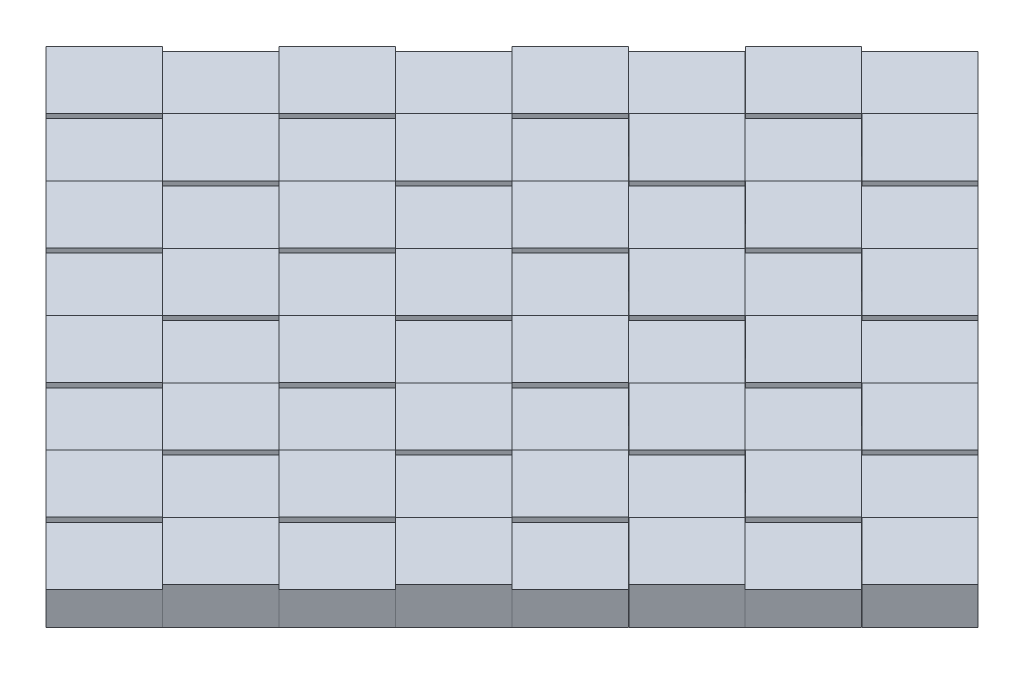
SolidWorks part; units mm, degrees
ref_plane "Front Plane" through (0, 0, 0) normal (0, 0, 1) x (1, 0, 0)
ref_plane "Top Plane" through (0, 0, 0) normal (0, 1, 0) x (1, 0, 0)
ref_plane "Right Plane" through (0, 0, 0) normal (1, 0, 0) x (0, 0, -1)
sketch "Sketch1" plane through (0, 0, 0) normal (0, 1, 0) x (1, 0, 0)
  line L0 (0, 0) -> (21.4596, 0) construction
  line L1 (150, 150) -> (-150, 150)
  line L2 (150, 150) -> (150, -150)
  line L3 (150, -150) -> (-150, -150)
  line L4 (-150, 150) -> (-150, -150)
  line L5 (0, 0) -> (0, 15.0297) construction
  dimension "D1" = 300
extrude "Boss-Extrude1" add sketch "Sketch1" along normal blind 15
sketch "Sketch6" plane through (0, 15, 0) normal (0, 1, 0) x (1, 0, 0)
  line L0 (150, 150) -> (-150, 150) construction
  line L1 (-150, 150) -> (-112.5, 150)
  line L2 (-150, 150) -> (-150, 112.5)
  line L3 (-150, 112.5) -> (-112.5, 112.5)
  line L4 (-112.5, 150) -> (-112.5, 112.5)
  line L5 (-112.49, 112.49) -> (-74.99, 112.49)
  line L6 (-112.49, 112.49) -> (-112.49, 74.99)
  line L7 (-112.49, 74.99) -> (-74.99, 74.99)
  line L8 (-74.99, 112.49) -> (-74.99, 74.99)
  line L9 (-74.98, 74.98) -> (-37.48, 74.98)
  line L10 (-74.98, 74.98) -> (-74.98, 37.48)
  line L11 (-74.98, 37.48) -> (-37.48, 37.48)
  line L12 (-37.48, 74.98) -> (-37.48, 37.48)
  line L13 (-37.47, 37.47) -> (0.03, 37.47)
  line L14 (-37.47, 37.47) -> (-37.47, -0.03)
  line L15 (-37.47, -0.03) -> (0.03, -0.03)
  line L16 (0.03, 37.47) -> (0.03, -0.03)
  line L17 (0.04, -0.04) -> (37.54, -0.04)
  line L18 (0.04, -0.04) -> (0.04, -37.54)
  line L19 (0.04, -37.54) -> (37.54, -37.54)
  line L20 (37.54, -0.04) -> (37.54, -37.54)
  line L21 (37.55, -37.55) -> (75.05, -37.55)
  line L22 (37.55, -37.55) -> (37.55, -75.05)
  line L23 (37.55, -75.05) -> (75.05, -75.05)
  line L24 (75.05, -37.55) -> (75.05, -75.05)
  line L25 (75.06, -75.06) -> (112.56, -75.06)
  line L26 (75.06, -75.06) -> (75.06, -112.56)
  line L27 (75.06, -112.56) -> (112.56, -112.56)
  line L28 (112.56, -75.06) -> (112.56, -112.56)
  line L29 (112.57, -112.57) -> (150.07, -112.57)
  line L30 (112.57, -112.57) -> (112.57, -150.07)
  line L31 (112.57, -150.07) -> (150.07, -150.07)
  line L32 (150.07, -112.57) -> (150.07, -150.07)
  line L33 (-74.98, 112.5) -> (-37.48, 112.5)
  line L34 (-74.98, 112.5) -> (-74.98, 150)
  line L35 (-74.98, 150) -> (-37.48, 150)
  line L36 (-37.48, 112.5) -> (-37.48, 150)
  line L37 (150, -150) -> (150, 150) construction
  line L38 (0.03, 74.99) -> (-37.47, 74.99)
  line L39 (0.03, 74.99) -> (0.03, 112.49)
  line L40 (0.03, 112.49) -> (-37.47, 112.49)
  line L41 (-37.47, 74.99) -> (-37.47, 112.49)
  line L42 (0.04, 74.98) -> (37.54, 74.98)
  line L43 (0.04, 74.98) -> (0.04, 37.48)
  line L44 (0.04, 37.48) -> (37.54, 37.48)
  line L45 (37.54, 74.98) -> (37.54, 37.48)
  line L46 (37.55, 37.47) -> (75.05, 37.47)
  line L47 (37.55, 37.47) -> (37.55, -0.03)
  line L48 (37.55, -0.03) -> (75.05, -0.03)
  line L49 (75.05, 37.47) -> (75.05, -0.03)
  line L50 (75.06, -0.04) -> (112.56, -0.04)
  line L51 (75.06, -0.04) -> (75.06, -37.54)
  line L52 (75.06, -37.54) -> (112.56, -37.54)
  line L53 (112.56, -0.04) -> (112.56, -37.54)
  line L54 (112.57, -37.55) -> (150, -37.55)
  line L55 (112.57, -37.55) -> (112.57, -75.05)
  line L56 (112.57, -75.05) -> (150, -75.05)
  line L57 (150, -37.55) -> (150, -75.05)
  line L58 (-150, 150) -> (-150, -150) construction
  line L59 (37.54, 150) -> (0.04, 150)
  line L60 (37.54, 150) -> (37.54, 112.5)
  line L61 (37.54, 112.5) -> (0.04, 112.5)
  line L62 (0.04, 150) -> (0.04, 112.5)
  line L63 (37.55, 112.49) -> (75.05, 112.49)
  line L64 (37.55, 112.49) -> (37.55, 74.99)
  line L65 (37.55, 74.99) -> (75.05, 74.99)
  line L66 (75.05, 112.49) -> (75.05, 74.99)
  line L67 (75.06, 74.98) -> (112.56, 74.98)
  line L68 (75.06, 74.98) -> (75.06, 37.48)
  line L69 (75.06, 37.48) -> (112.56, 37.48)
  line L70 (112.56, 74.98) -> (112.56, 37.48)
  line L71 (112.57, 37.47) -> (150, 37.47)
  line L72 (112.57, 37.47) -> (112.57, -0.03)
  line L73 (112.57, -0.03) -> (150, -0.03)
  line L74 (150, 37.47) -> (150, -0.03)
  line L75 (112.56, 150) -> (75.06, 150)
  line L76 (112.56, 150) -> (112.56, 112.5)
  line L77 (112.56, 112.5) -> (75.06, 112.5)
  line L78 (75.06, 150) -> (75.06, 112.5)
  line L79 (150, 112.49) -> (112.57, 112.49)
  line L80 (150, 112.49) -> (150, 74.99)
  line L81 (150, 74.99) -> (112.57, 74.99)
  line L82 (112.57, 112.49) -> (112.57, 74.99)
  line L83 (-112.5, 74.98) -> (-150, 74.98)
  line L84 (-112.5, 74.98) -> (-112.5, 37.48)
  line L85 (-112.5, 37.48) -> (-150, 37.48)
  line L86 (-150, 74.98) -> (-150, 37.48)
  line L87 (-74.99, 37.47) -> (-112.49, 37.47)
  line L88 (-74.99, 37.47) -> (-74.99, -0.03)
  line L89 (-74.99, -0.03) -> (-112.49, -0.03)
  line L90 (-112.49, 37.47) -> (-112.49, -0.03)
  line L91 (-37.48, -0.04) -> (-74.98, -0.04)
  line L92 (-37.48, -0.04) -> (-37.48, -37.54)
  line L93 (-37.48, -37.54) -> (-74.98, -37.54)
  line L94 (-74.98, -0.04) -> (-74.98, -37.54)
  line L95 (0.03, -37.55) -> (-37.47, -37.55)
  line L96 (0.03, -37.55) -> (0.03, -75.05)
  line L97 (0.03, -75.05) -> (-37.47, -75.05)
  line L98 (-37.47, -37.55) -> (-37.47, -75.05)
  line L99 (37.54, -75.06) -> (0.04, -75.06)
  line L100 (37.54, -75.06) -> (37.54, -112.56)
  line L101 (37.54, -112.56) -> (0.04, -112.56)
  line L102 (0.04, -75.06) -> (0.04, -112.56)
  line L103 (75.05, -112.57) -> (37.55, -112.57)
  line L104 (75.05, -112.57) -> (75.05, -150.07)
  line L105 (75.05, -150.07) -> (37.55, -150.07)
  line L106 (37.55, -112.57) -> (37.55, -150.07)
  line L108 (-112.5, -0.04) -> (-150, -0.04)
  line L109 (-112.5, -0.04) -> (-112.5, -37.54)
  line L110 (-112.5, -37.54) -> (-150, -37.54)
  line L111 (-150, -0.04) -> (-150, -37.54)
  line L112 (-74.99, -37.55) -> (-112.49, -37.55)
  line L113 (-74.99, -37.55) -> (-74.99, -75.05)
  line L114 (-74.99, -75.05) -> (-112.49, -75.05)
  line L115 (-112.49, -37.55) -> (-112.49, -75.05)
  line L116 (-37.48, -75.06) -> (-74.98, -75.06)
  line L117 (-37.48, -75.06) -> (-37.48, -112.56)
  line L118 (-37.48, -112.56) -> (-74.98, -112.56)
  line L119 (-74.98, -75.06) -> (-74.98, -112.56)
  line L120 (0.03, -112.57) -> (-37.47, -112.57)
  line L121 (0.03, -112.57) -> (0.03, -150.07)
  line L122 (0.03, -150.07) -> (-37.47, -150.07)
  line L123 (-37.47, -112.57) -> (-37.47, -150.07)
  line L124 (-74.99, -112.57) -> (-112.49, -112.57)
  line L125 (-74.99, -112.57) -> (-74.99, -150.07)
  line L126 (-74.99, -150.07) -> (-112.49, -150.07)
  line L127 (-112.49, -112.57) -> (-112.49, -150.07)
  line L128 (-112.5, -75.06) -> (-150, -75.06)
  line L129 (-112.5, -75.06) -> (-112.5, -112.56)
  line L130 (-112.5, -112.56) -> (-150, -112.56)
  line L131 (-150, -75.06) -> (-150, -112.56)
  dimension "D1" = 37.5
  dimension "D2" = 37.5
  dimension "D3" = 0.01
  dimension "D4" = 0.01
  dimension "D5" = 0.01
  dimension "D6" = 0.01
  dimension "D7" = 0.01
  dimension "D8" = 0.01
  dimension "D9" = 0.01
  dimension "D10" = 0.01
  dimension "D11" = 0.01
  dimension "D12" = 0.01
  dimension "D13" = 0.01
  dimension "D14" = 0.01
  dimension "D15" = 0.01
  dimension "D16" = 0.01
extrude "Cut-Extrude2" cut sketch "Sketch6" against normal blind 100
sketch "Sketch7" plane through (0, 0, 0) normal (0, 1, 0) x (1, 0, 0)
  line L0 (-74.98, 150) -> (-112.5, 150) construction
  line L1 (-112.55, 149.95) -> (-149.95, 149.95)
  line L2 (-112.55, 149.95) -> (-112.55, 112.55)
  line L3 (-112.55, 112.55) -> (-149.95, 112.55)
  line L4 (-149.95, 149.95) -> (-149.95, 112.55)
  line L5 (-150, 112.5) -> (-150, 74.98) construction
  line L6 (-150, 112.5) -> (-112.5, 112.5) construction
  line L7 (-112.5, 112.5) -> (-112.5, 150) construction
  line L8 (-75.04, 149.95) -> (-112.44, 149.95) [skipped]
  line L9 (-75.04, 149.95) -> (-75.04, 112.55) [skipped]
  line L10 (-75.04, 112.55) -> (-112.44, 112.55) [skipped]
  line L11 (-112.44, 149.95) -> (-112.44, 112.55) [skipped]
  line L12 (-37.53, 149.95) -> (-74.93, 149.95)
  line L13 (-37.53, 149.95) -> (-37.53, 112.55)
  line L14 (-37.53, 112.55) -> (-74.93, 112.55)
  line L15 (-74.93, 149.95) -> (-74.93, 112.55)
  line L16 (-0.02, 149.95) -> (-37.42, 149.95) [skipped]
  line L17 (-0.02, 149.95) -> (-0.02, 112.55) [skipped]
  line L18 (-0.02, 112.55) -> (-37.42, 112.55) [skipped]
  line L19 (-37.42, 149.95) -> (-37.42, 112.55) [skipped]
  line L20 (37.49, 149.95) -> (0.09, 149.95)
  line L21 (37.49, 149.95) -> (37.49, 112.55)
  line L22 (37.49, 112.55) -> (0.09, 112.55)
  line L23 (0.09, 149.95) -> (0.09, 112.55)
  line L24 (75, 149.95) -> (37.6, 149.95) [skipped]
  line L25 (75, 149.95) -> (75, 112.55) [skipped]
  line L26 (75, 112.55) -> (37.6, 112.55) [skipped]
  line L27 (37.6, 149.95) -> (37.6, 112.55) [skipped]
  line L28 (112.51, 149.95) -> (75.11, 149.95)
  line L29 (112.51, 149.95) -> (112.51, 112.55)
  line L30 (112.51, 112.55) -> (75.11, 112.55)
  line L31 (75.11, 149.95) -> (75.11, 112.55)
  line L32 (150.02, 149.95) -> (112.62, 149.95) [skipped]
  line L33 (150.02, 149.95) -> (150.02, 112.55) [skipped]
  line L34 (150.02, 112.55) -> (112.62, 112.55) [skipped]
  line L35 (112.62, 149.95) -> (112.62, 112.55) [skipped]
  line L36 (-75.04, 112.44) -> (-112.44, 112.44)
  line L37 (-75.04, 112.44) -> (-75.04, 75.04)
  line L38 (-75.04, 75.04) -> (-112.44, 75.04)
  line L39 (-112.44, 112.44) -> (-112.44, 75.04)
  line L40 (-37.53, 112.44) -> (-74.93, 112.44) [skipped]
  line L41 (-37.53, 112.44) -> (-37.53, 75.04) [skipped]
  line L42 (-37.53, 75.04) -> (-74.93, 75.04) [skipped]
  line L43 (-74.93, 112.44) -> (-74.93, 75.04) [skipped]
  line L44 (-0.02, 112.44) -> (-37.42, 112.44)
  line L45 (-0.02, 112.44) -> (-0.02, 75.04)
  line L46 (-0.02, 75.04) -> (-37.42, 75.04)
  line L47 (-37.42, 112.44) -> (-37.42, 75.04)
  line L48 (37.49, 112.44) -> (0.09, 112.44) [skipped]
  line L49 (37.49, 112.44) -> (37.49, 75.04) [skipped]
  line L50 (37.49, 75.04) -> (0.09, 75.04) [skipped]
  line L51 (0.09, 112.44) -> (0.09, 75.04) [skipped]
  line L52 (75, 112.44) -> (37.6, 112.44)
  line L53 (75, 112.44) -> (75, 75.04)
  line L54 (75, 75.04) -> (37.6, 75.04)
  line L55 (37.6, 112.44) -> (37.6, 75.04)
  line L56 (112.51, 112.44) -> (75.11, 112.44) [skipped]
  line L57 (112.51, 112.44) -> (112.51, 75.04) [skipped]
  line L58 (112.51, 75.04) -> (75.11, 75.04) [skipped]
  line L59 (75.11, 112.44) -> (75.11, 75.04) [skipped]
  line L60 (150.02, 112.44) -> (112.62, 112.44)
  line L61 (150.02, 112.44) -> (150.02, 75.04)
  line L62 (150.02, 75.04) -> (112.62, 75.04)
  line L63 (112.62, 112.44) -> (112.62, 75.04)
  line L64 (-75.04, 74.93) -> (-112.44, 74.93) [skipped]
  line L65 (-75.04, 74.93) -> (-75.04, 37.53) [skipped]
  line L66 (-75.04, 37.53) -> (-112.44, 37.53) [skipped]
  line L67 (-112.44, 74.93) -> (-112.44, 37.53) [skipped]
  line L68 (-37.53, 74.93) -> (-74.93, 74.93)
  line L69 (-37.53, 74.93) -> (-37.53, 37.53)
  line L70 (-37.53, 37.53) -> (-74.93, 37.53)
  line L71 (-74.93, 74.93) -> (-74.93, 37.53)
  line L72 (-0.02, 74.93) -> (-37.42, 74.93) [skipped]
  line L73 (-0.02, 74.93) -> (-0.02, 37.53) [skipped]
  line L74 (-0.02, 37.53) -> (-37.42, 37.53) [skipped]
  line L75 (-37.42, 74.93) -> (-37.42, 37.53) [skipped]
  line L76 (37.49, 74.93) -> (0.09, 74.93)
  line L77 (37.49, 74.93) -> (37.49, 37.53)
  line L78 (37.49, 37.53) -> (0.09, 37.53)
  line L79 (0.09, 74.93) -> (0.09, 37.53)
  line L80 (75, 74.93) -> (37.6, 74.93) [skipped]
  line L81 (75, 74.93) -> (75, 37.53) [skipped]
  line L82 (75, 37.53) -> (37.6, 37.53) [skipped]
  line L83 (37.6, 74.93) -> (37.6, 37.53) [skipped]
  line L84 (112.51, 74.93) -> (75.11, 74.93)
  line L85 (112.51, 74.93) -> (112.51, 37.53)
  line L86 (112.51, 37.53) -> (75.11, 37.53)
  line L87 (75.11, 74.93) -> (75.11, 37.53)
  line L88 (150.02, 74.93) -> (112.62, 74.93) [skipped]
  line L89 (150.02, 74.93) -> (150.02, 37.53) [skipped]
  line L90 (150.02, 37.53) -> (112.62, 37.53) [skipped]
  line L91 (112.62, 74.93) -> (112.62, 37.53) [skipped]
  line L92 (-75.04, 37.42) -> (-112.44, 37.42)
  line L93 (-75.04, 37.42) -> (-75.04, 0.02)
  line L94 (-75.04, 0.02) -> (-112.44, 0.02)
  line L95 (-112.44, 37.42) -> (-112.44, 0.02)
  line L96 (-37.53, 37.42) -> (-74.93, 37.42) [skipped]
  line L97 (-37.53, 37.42) -> (-37.53, 0.02) [skipped]
  line L98 (-37.53, 0.02) -> (-74.93, 0.02) [skipped]
  line L99 (-74.93, 37.42) -> (-74.93, 0.02) [skipped]
  line L100 (-0.02, 37.42) -> (-37.42, 37.42)
  line L101 (-0.02, 37.42) -> (-0.02, 0.02)
  line L102 (-0.02, 0.02) -> (-37.42, 0.02)
  line L103 (-37.42, 37.42) -> (-37.42, 0.02)
  line L104 (37.49, 37.42) -> (0.09, 37.42) [skipped]
  line L105 (37.49, 37.42) -> (37.49, 0.02) [skipped]
  line L106 (37.49, 0.02) -> (0.09, 0.02) [skipped]
  line L107 (0.09, 37.42) -> (0.09, 0.02) [skipped]
  line L108 (75, 37.42) -> (37.6, 37.42)
  line L109 (75, 37.42) -> (75, 0.02)
  line L110 (75, 0.02) -> (37.6, 0.02)
  line L111 (37.6, 37.42) -> (37.6, 0.02)
  line L112 (112.51, 37.42) -> (75.11, 37.42) [skipped]
  line L113 (112.51, 37.42) -> (112.51, 0.02) [skipped]
  line L114 (112.51, 0.02) -> (75.11, 0.02) [skipped]
  line L115 (75.11, 37.42) -> (75.11, 0.02) [skipped]
  line L116 (150.02, 37.42) -> (112.62, 37.42)
  line L117 (150.02, 37.42) -> (150.02, 0.02)
  line L118 (150.02, 0.02) -> (112.62, 0.02)
  line L119 (112.62, 37.42) -> (112.62, 0.02)
  line L120 (-75.04, -0.09) -> (-112.44, -0.09) [skipped]
  line L121 (-75.04, -0.09) -> (-75.04, -37.49) [skipped]
  line L122 (-75.04, -37.49) -> (-112.44, -37.49) [skipped]
  line L123 (-112.44, -0.09) -> (-112.44, -37.49) [skipped]
  line L124 (-37.53, -0.09) -> (-74.93, -0.09)
  line L125 (-37.53, -0.09) -> (-37.53, -37.49)
  line L126 (-37.53, -37.49) -> (-74.93, -37.49)
  line L127 (-74.93, -0.09) -> (-74.93, -37.49)
  line L128 (-0.02, -0.09) -> (-37.42, -0.09) [skipped]
  line L129 (-0.02, -0.09) -> (-0.02, -37.49) [skipped]
  line L130 (-0.02, -37.49) -> (-37.42, -37.49) [skipped]
  line L131 (-37.42, -0.09) -> (-37.42, -37.49) [skipped]
  line L132 (37.49, -0.09) -> (0.09, -0.09)
  line L133 (37.49, -0.09) -> (37.49, -37.49)
  line L134 (37.49, -37.49) -> (0.09, -37.49)
  line L135 (0.09, -0.09) -> (0.09, -37.49)
  line L136 (75, -0.09) -> (37.6, -0.09) [skipped]
  line L137 (75, -0.09) -> (75, -37.49) [skipped]
  line L138 (75, -37.49) -> (37.6, -37.49) [skipped]
  line L139 (37.6, -0.09) -> (37.6, -37.49) [skipped]
  line L140 (112.51, -0.09) -> (75.11, -0.09)
  line L141 (112.51, -0.09) -> (112.51, -37.49)
  line L142 (112.51, -37.49) -> (75.11, -37.49)
  line L143 (75.11, -0.09) -> (75.11, -37.49)
  line L144 (150.02, -0.09) -> (112.62, -0.09) [skipped]
  line L145 (150.02, -0.09) -> (150.02, -37.49) [skipped]
  line L146 (150.02, -37.49) -> (112.62, -37.49) [skipped]
  line L147 (112.62, -0.09) -> (112.62, -37.49) [skipped]
  line L148 (-75.04, -37.6) -> (-112.44, -37.6)
  line L149 (-75.04, -37.6) -> (-75.04, -75)
  line L150 (-75.04, -75) -> (-112.44, -75)
  line L151 (-112.44, -37.6) -> (-112.44, -75)
  line L152 (-37.53, -37.6) -> (-74.93, -37.6) [skipped]
  line L153 (-37.53, -37.6) -> (-37.53, -75) [skipped]
  line L154 (-37.53, -75) -> (-74.93, -75) [skipped]
  line L155 (-74.93, -37.6) -> (-74.93, -75) [skipped]
  line L156 (-0.02, -37.6) -> (-37.42, -37.6)
  line L157 (-0.02, -37.6) -> (-0.02, -75)
  line L158 (-0.02, -75) -> (-37.42, -75)
  line L159 (-37.42, -37.6) -> (-37.42, -75)
  line L160 (37.49, -37.6) -> (0.09, -37.6) [skipped]
  line L161 (37.49, -37.6) -> (37.49, -75) [skipped]
  line L162 (37.49, -75) -> (0.09, -75) [skipped]
  line L163 (0.09, -37.6) -> (0.09, -75) [skipped]
  line L164 (75, -37.6) -> (37.6, -37.6)
  line L165 (75, -37.6) -> (75, -75)
  line L166 (75, -75) -> (37.6, -75)
  line L167 (37.6, -37.6) -> (37.6, -75)
  line L168 (112.51, -37.6) -> (75.11, -37.6) [skipped]
  line L169 (112.51, -37.6) -> (112.51, -75) [skipped]
  line L170 (112.51, -75) -> (75.11, -75) [skipped]
  line L171 (75.11, -37.6) -> (75.11, -75) [skipped]
  line L172 (150.02, -37.6) -> (112.62, -37.6)
  line L173 (150.02, -37.6) -> (150.02, -75)
  line L174 (150.02, -75) -> (112.62, -75)
  line L175 (112.62, -37.6) -> (112.62, -75)
  line L176 (-75.04, -75.11) -> (-112.44, -75.11) [skipped]
  line L177 (-75.04, -75.11) -> (-75.04, -112.51) [skipped]
  line L178 (-75.04, -112.51) -> (-112.44, -112.51) [skipped]
  line L179 (-112.44, -75.11) -> (-112.44, -112.51) [skipped]
  line L180 (-37.53, -75.11) -> (-74.93, -75.11)
  line L181 (-37.53, -75.11) -> (-37.53, -112.51)
  line L182 (-37.53, -112.51) -> (-74.93, -112.51)
  line L183 (-74.93, -75.11) -> (-74.93, -112.51)
  line L184 (-0.02, -75.11) -> (-37.42, -75.11) [skipped]
  line L185 (-0.02, -75.11) -> (-0.02, -112.51) [skipped]
  line L186 (-0.02, -112.51) -> (-37.42, -112.51) [skipped]
  line L187 (-37.42, -75.11) -> (-37.42, -112.51) [skipped]
  line L188 (37.49, -75.11) -> (0.09, -75.11)
  line L189 (37.49, -75.11) -> (37.49, -112.51)
  line L190 (37.49, -112.51) -> (0.09, -112.51)
  line L191 (0.09, -75.11) -> (0.09, -112.51)
  line L192 (75, -75.11) -> (37.6, -75.11) [skipped]
  line L193 (75, -75.11) -> (75, -112.51) [skipped]
  line L194 (75, -112.51) -> (37.6, -112.51) [skipped]
  line L195 (37.6, -75.11) -> (37.6, -112.51) [skipped]
  line L196 (112.51, -75.11) -> (75.11, -75.11)
  line L197 (112.51, -75.11) -> (112.51, -112.51)
  line L198 (112.51, -112.51) -> (75.11, -112.51)
  line L199 (75.11, -75.11) -> (75.11, -112.51)
  line L200 (150.02, -75.11) -> (112.62, -75.11) [skipped]
  line L201 (150.02, -75.11) -> (150.02, -112.51) [skipped]
  line L202 (150.02, -112.51) -> (112.62, -112.51) [skipped]
  line L203 (112.62, -75.11) -> (112.62, -112.51) [skipped]
  line L204 (-75.04, -112.62) -> (-112.44, -112.62)
  line L205 (-75.04, -112.62) -> (-75.04, -150.02)
  line L206 (-75.04, -150.02) -> (-112.44, -150.02)
  line L207 (-112.44, -112.62) -> (-112.44, -150.02)
  line L208 (-37.53, -112.62) -> (-74.93, -112.62) [skipped]
  line L209 (-37.53, -112.62) -> (-37.53, -150.02) [skipped]
  line L210 (-37.53, -150.02) -> (-74.93, -150.02) [skipped]
  line L211 (-74.93, -112.62) -> (-74.93, -150.02) [skipped]
  line L212 (-0.02, -112.62) -> (-37.42, -112.62)
  line L213 (-0.02, -112.62) -> (-0.02, -150.02)
  line L214 (-0.02, -150.02) -> (-37.42, -150.02)
  line L215 (-37.42, -112.62) -> (-37.42, -150.02)
  line L216 (37.49, -112.62) -> (0.09, -112.62) [skipped]
  line L217 (37.49, -112.62) -> (37.49, -150.02) [skipped]
  line L218 (37.49, -150.02) -> (0.09, -150.02) [skipped]
  line L219 (0.09, -112.62) -> (0.09, -150.02) [skipped]
  line L220 (75, -112.62) -> (37.6, -112.62)
  line L221 (75, -112.62) -> (75, -150.02)
  line L222 (75, -150.02) -> (37.6, -150.02)
  line L223 (37.6, -112.62) -> (37.6, -150.02)
  line L224 (112.51, -112.62) -> (75.11, -112.62) [skipped]
  line L225 (112.51, -112.62) -> (112.51, -150.02) [skipped]
  line L226 (112.51, -150.02) -> (75.11, -150.02) [skipped]
  line L227 (75.11, -112.62) -> (75.11, -150.02) [skipped]
  line L228 (150.02, -112.62) -> (112.62, -112.62)
  line L229 (150.02, -112.62) -> (150.02, -150.02)
  line L230 (150.02, -150.02) -> (112.62, -150.02)
  line L231 (112.62, -112.62) -> (112.62, -150.02)
  line L232 (-112.55, 112.44) -> (-149.95, 112.44) [skipped]
  line L233 (-112.55, 112.44) -> (-112.55, 75.04) [skipped]
  line L234 (-112.55, 75.04) -> (-149.95, 75.04) [skipped]
  line L235 (-149.95, 112.44) -> (-149.95, 75.04) [skipped]
  line L236 (-112.55, 74.93) -> (-149.95, 74.93)
  line L237 (-112.55, 74.93) -> (-112.55, 37.53)
  line L238 (-112.55, 37.53) -> (-149.95, 37.53)
  line L239 (-149.95, 74.93) -> (-149.95, 37.53)
  line L240 (-112.55, 37.42) -> (-149.95, 37.42) [skipped]
  line L241 (-112.55, 37.42) -> (-112.55, 0.02) [skipped]
  line L242 (-112.55, 0.02) -> (-149.95, 0.02) [skipped]
  line L243 (-149.95, 37.42) -> (-149.95, 0.02) [skipped]
  line L244 (-112.55, -0.09) -> (-149.95, -0.09)
  line L245 (-112.55, -0.09) -> (-112.55, -37.49)
  line L246 (-112.55, -37.49) -> (-149.95, -37.49)
  line L247 (-149.95, -0.09) -> (-149.95, -37.49)
  line L248 (-112.55, -37.6) -> (-149.95, -37.6) [skipped]
  line L249 (-112.55, -37.6) -> (-112.55, -75) [skipped]
  line L250 (-112.55, -75) -> (-149.95, -75) [skipped]
  line L251 (-149.95, -37.6) -> (-149.95, -75) [skipped]
  line L252 (-112.55, -75.11) -> (-149.95, -75.11)
  line L253 (-112.55, -75.11) -> (-112.55, -112.51)
  line L254 (-112.55, -112.51) -> (-149.95, -112.51)
  line L255 (-149.95, -75.11) -> (-149.95, -112.51)
  line L256 (-112.55, -112.62) -> (-149.95, -112.62) [skipped]
  line L257 (-112.55, -112.62) -> (-112.55, -150.02) [skipped]
  line L258 (-112.55, -150.02) -> (-149.95, -150.02) [skipped]
  line L259 (-149.95, -112.62) -> (-149.95, -150.02) [skipped]
  dimension "D1" = 0.05
  dimension "D2" = 0.05
  dimension "D3" = 0.05
  dimension "D4" = 0.05
  dimension "D5" = 8
  dimension "D6" = 8
extrude "Boss-Extrude2" add sketch "Sketch7" along normal blind 17 separate body
move or copy body "Body-Move/Copy1" bodies to move or copy 145 173 107 172 169 166 159 162 165 168 171 170 167 164 161 158 155 152 148 151 154 157 160 163 176 175 156 153 150 147 146 149 174 copy no rotation origin (0.0339, 0, 0.0339) rotation axis (0, 1, 0) rotation angle 45
